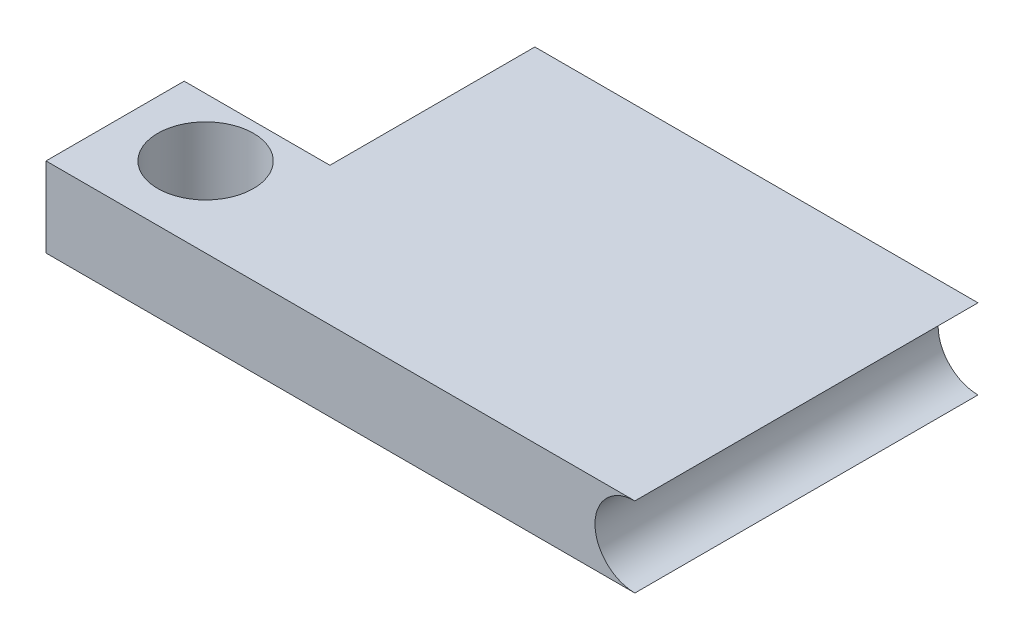
SolidWorks part; units mm, degrees
ref_plane "Front Plane" through (0, 0, 0) normal (0, 0, 1) x (1, 0, 0)
ref_plane "Top Plane" through (0, 0, 0) normal (0, 1, 0) x (1, 0, 0)
ref_plane "Right Plane" through (0, 0, 0) normal (1, 0, 0) x (0, 0, -1)
sketch "Sketch1" plane through (0, 0, 0) normal (0, 0, 1) x (1, 0, 0)
  line L0 (0, 150) -> (0, 0)
  line L1 (0, 150) -> (1106.9725, 150)
  line L3 (0, 0) -> (1106.9725, 0)
  line L4 (1106.9725, 150) -> (1106.9725, 0)
extrude "Boss-Extrude1" add sketch "Sketch1" along normal blind 645 contours L1 L4 L3 L0
sketch "Sketch2" plane through (0, 0, 0) normal (0, -1, 0) x (1, 0, 0)
  line L0 (0, 645) -> (0, 0) construction
  line L1 (0, 645) -> (1106.9725, 645) construction
  circle A0 centre (150, 495) radius 90
  dimension "D1" = 180
  dimension "D2" = 150
  dimension "D3" = 150
extrude "Cut-Extrude1" cut sketch "Sketch2" against normal through all contours A0
sketch "Sketch3" plane through (0, 0, 0) normal (0, -1, 0) x (1, 0, 0)
  line L1 (0, 0) -> (273.9363, 0)
  line L2 (0, 0) -> (0, 385.2587)
  line L3 (0, 385.2587) -> (273.9363, 385.2587)
  line L4 (273.9363, 0) -> (273.9363, 385.2587)
extrude "Cut-Extrude2" cut sketch "Sketch3" against normal through all
sketch "Sketch5" plane through (0, 0, 645) normal (0, 0, 1) x (1, 0, 0)
  line L0 (1106.9725, 150) -> (1106.9725, 0) construction
  line L2 (1106.9725, 150) -> (1106.9725, 0)
  arc A0 (1106.9725, 0) -> (1106.9725, 150) centre (1106.9725, 75) cw
extrude "Cut-Extrude3" cut sketch "Sketch5" against normal through all
